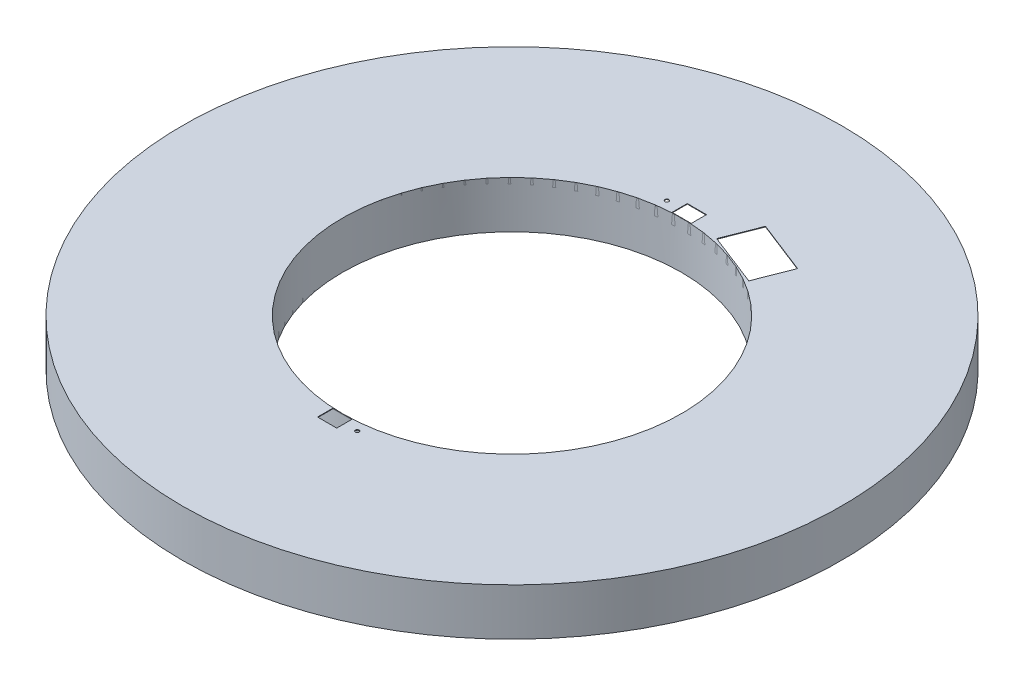
SolidWorks part; units mm, degrees
material "1345 Alloy"
ref_plane "Front Plane" through (0, 0, 0) normal (0, 0, 1) x (1, 0, 0)
ref_plane "Top Plane" through (0, 0, 0) normal (0, 1, 0) x (1, 0, 0)
ref_plane "Right Plane" through (0, 0, 0) normal (1, 0, 0) x (0, 0, -1)
sketch "Sketch1" plane through (0, 0, 0) normal (0, 1, 0) x (1, 0, 0)
  circle A0 centre (0, 0) radius 1750
extrude "Boss-Extrude1" add sketch "Sketch1" along normal blind 500
sketch "Sketch2" plane through (0, 500, 0) normal (0, 1, 0) x (1, 0, 0)
  circle A0 centre (0, 0) radius 900
extrude "Cut-Extrude2" cut sketch "Sketch2" against normal blind 300
sketch "Sketch3" plane through (0, 0, 0) normal (0, -1, 0) x (1, 0, 0)
  circle A0 centre (0, 0) radius 600
extrude "Cut-Extrude3" cut sketch "Sketch3" against normal blind 300
sketch "Sketch4" plane through (0, 0, 0) normal (0, -1, 0) x (-1, 0, 0)
  circle A0 centre (0, 0) radius 900.75
  circle A1 centre (0, 0) radius 1748.5
extrude "Cut-Extrude5" cut sketch "Sketch4" against normal blind 497
sketch "Sketch5" plane through (0, 0, 0) normal (0, 0, 1) x (1, 0, 0)
  line L0 (0, 0) -> (0, 250)
  line L1 (0, 250) -> (1750, 250)
  line L2 (1750, 0) -> (1750, 500) construction
  line L3 (1750, 250) -> (1750, 0)
  line L4 (1750, 0) -> (-1750, 0)
  line L5 (-1750, 0) -> (-1750, 250)
  line L6 (-1750, 500) -> (-1750, 0) construction
  line L7 (-1750, 250) -> (0, 250)
extrude "Cut-Extrude6" cut sketch "Sketch5" against normal through all both and the other way through all contours L7 L5 L4 L0 | L4 L3 L1 L0
sketch "Sketch6" plane through (0, 497, 0) normal (0, -1, 0) x (1, 0, 0)
  line L0 (0, 900.75) -> (51, 900.75)
  line L1 (51, 900.75) -> (51, 981.75)
  line L2 (51, 981.75) -> (-51, 981.75)
  line L3 (-51, 981.75) -> (-51, 900.75)
  line L4 (-51, 900.75) -> (0, 900.75)
  circle A0 centre (0, 0) radius 900.75 construction
  circle A1 centre (0, 0) radius 900.75 construction
extrude "Cut-Extrude7" cut sketch "Sketch6" against normal blind 10
pattern_circular "CirPattern1" count 2 every 180 about axis through (0, 0, 0) along (0, 1, 0) of "Cut-Extrude7"
sketch "Sketch7" plane through (0, 497, 0) normal (0, -1, 0) x (1, 0, 0)
  circle A0 centre (-118.8186, -941.25) radius 10
  circle A1 centre (119.3007, 941.189) radius 10
  dimension "D1" = 2
extrude "Cut-Extrude8" cut sketch "Sketch7" against normal blind 10
sketch "Sketch8" plane through (0, 497, 0) normal (0, -1, 0) x (1, 0, 0)
  line L0 (188.595, -898.4454) -> (468.0462, -789.3263)
  line L1 (188.595, -898.4454) -> (261.341, -1084.7463)
  line L2 (261.341, -1084.7463) -> (540.7923, -975.6272)
  line L3 (468.0462, -789.3263) -> (540.7923, -975.6272)
extrude "Cut-Extrude9" cut sketch "Sketch8" against normal blind 10
